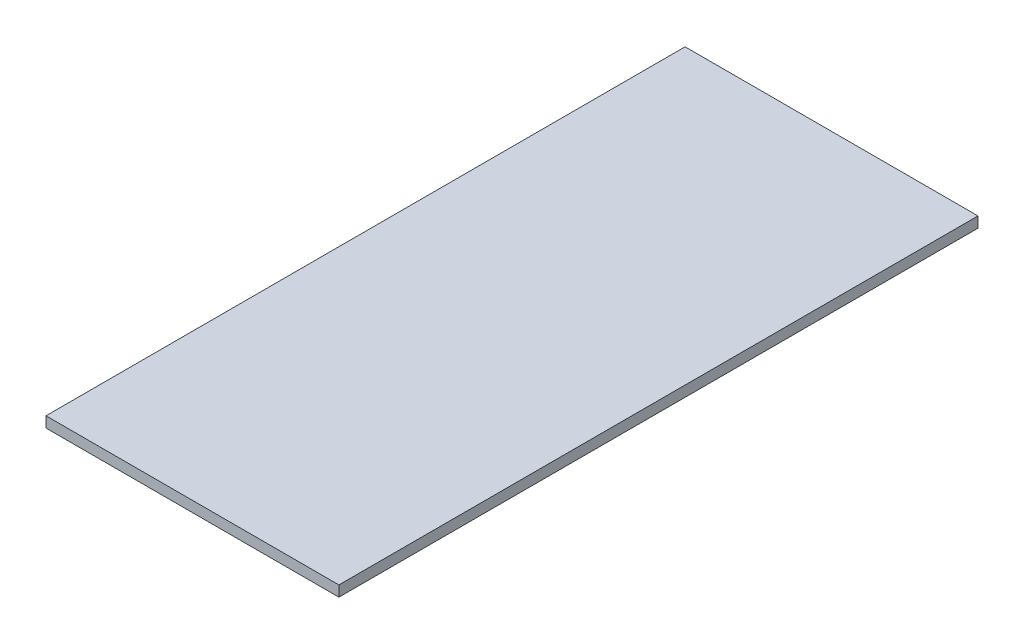
SolidWorks part; units mm, degrees
ref_plane "Front Plane" through (0, 0, 0) normal (0, 0, 1) x (1, 0, 0)
ref_plane "Top Plane" through (0, 0, 0) normal (0, 1, 0) x (1, 0, 0)
ref_plane "Right Plane" through (0, 0, 0) normal (1, 0, 0) x (0, 0, -1)
sketch "Sketch1" plane through (0, 0, 0) normal (0, 1, 0) x (1, 0, 0)
  line L1 (-30, 1147.651) -> (520, 1147.651)
  line L2 (-30, 1147.651) -> (-30, -52.349)
  line L3 (-30, -52.349) -> (520, -52.349)
  line L4 (520, 1147.651) -> (520, -52.349)
  dimension "D1" = 1200
  dimension "D2" = 550
extrude "Boss-Extrude1" add sketch "Sketch1" along normal blind 20
